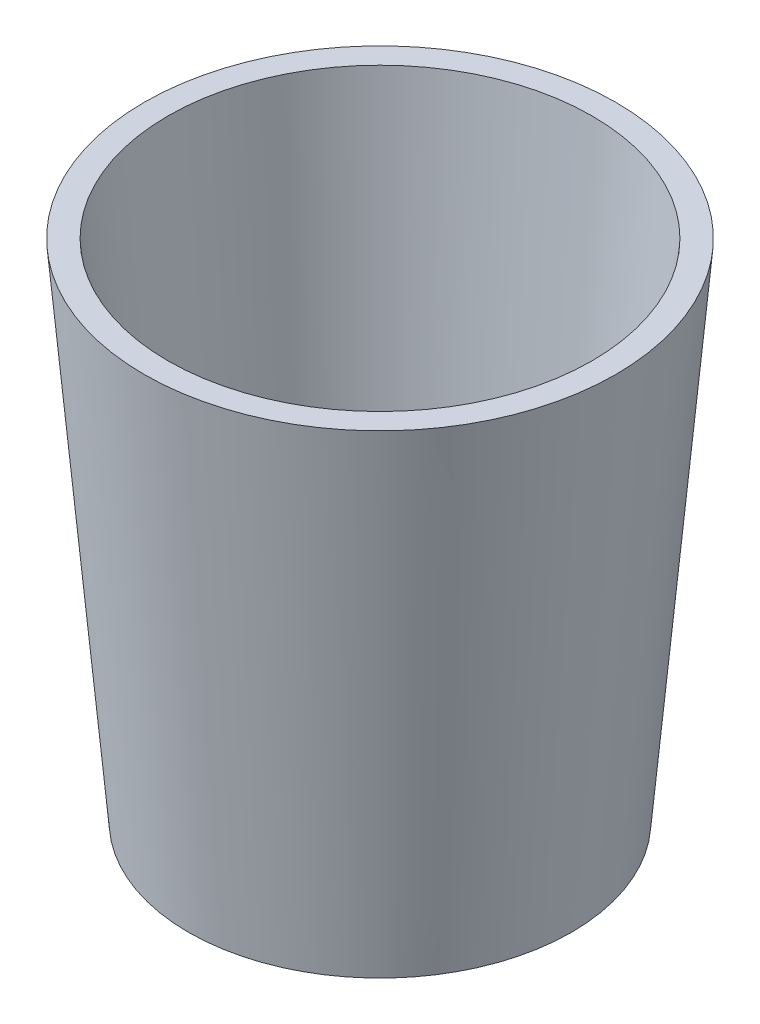
SolidWorks part; units mm, degrees
ref_plane "前视基准面" through (0, 0, 0) normal (0, 0, 1) x (1, 0, 0)
ref_plane "上视基准面" through (0, 0, 0) normal (0, 1, 0) x (1, 0, 0)
ref_plane "右视基准面" through (0, 0, 0) normal (1, 0, 0) x (0, 0, -1)
other "Configuration Table"
sketch "草图1" plane through (0, 0, 0) normal (0, 0, 1) x (1, 0, 0)
  line L0 (0, 0) -> (56.8767, 0)
  line L1 (56.8767, 0) -> (56.8767, 20)
  line L2 (56.8767, 20) -> (5.277, 20)
  line L3 (5.277, 20) -> (-6.0966, 150)
  line L4 (-6.0966, 150) -> (-13.1233, 150)
  line L5 (-13.1233, 150) -> (0, 0)
  point P3 (0, 0)
  point P8 (0, 0)
  point P9 (55.9677, 1.8548)
  dimension "D1" = 70
  dimension "D2" = 20
  dimension "D3" = 150
  dimension "D4" = 7
  dimension "D5" = 85
revolve "旋转1" add sketch "草图1" angle 360 about L1
